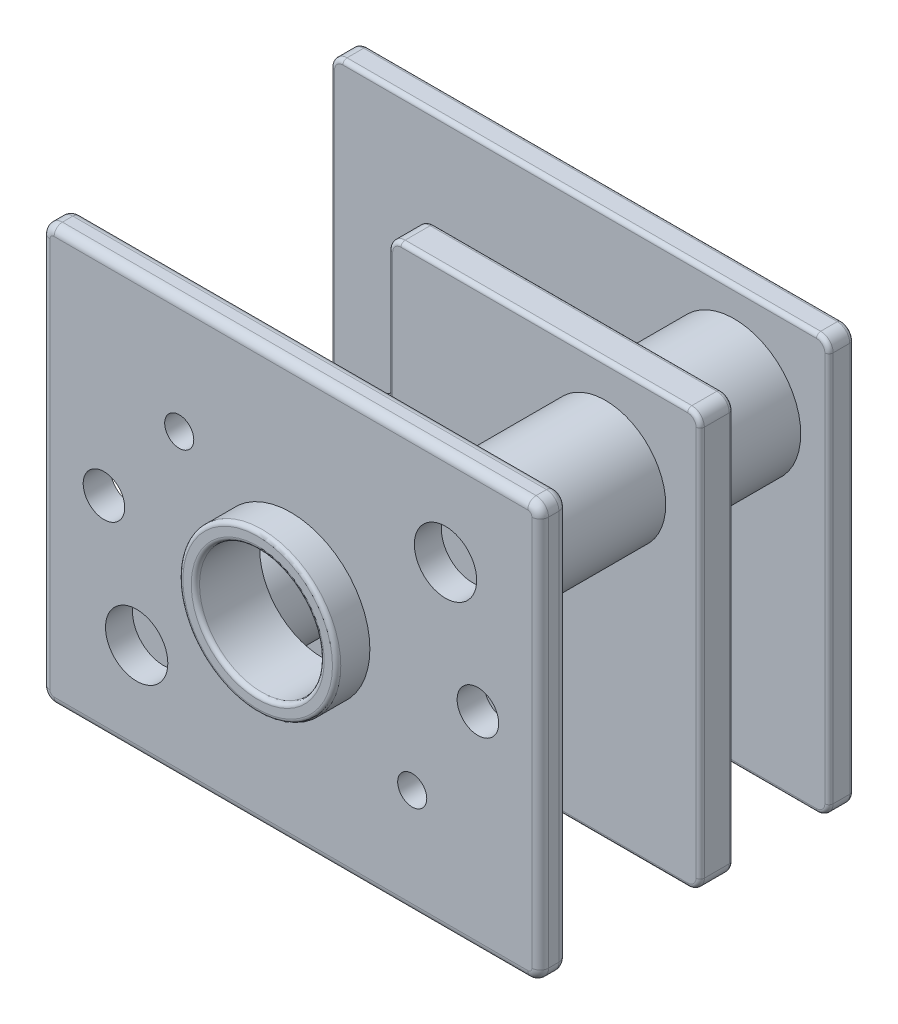
SolidWorks part; units mm, degrees
ref_plane "Front Plane" through (0, 0, 0) normal (0, 0, 1) x (1, 0, 0)
ref_plane "Top Plane" through (0, 0, 0) normal (0, 1, 0) x (1, 0, 0)
ref_plane "Right Plane" through (0, 0, 0) normal (1, 0, 0) x (0, 0, -1)
sketch "Sketch1" plane through (0, 0, 0) normal (0, 0, 1) x (1, 0, 0)
  line L0 (0.369, -5) -> (6, -5)
  line L1 (-6, 5) -> (6, 5)
  line L2 (-6, 5) -> (-6, -5)
  line L3 (-6, -5) -> (-0.369, -5)
  line L4 (6, 5) -> (6, -5)
  line L5 (-6, 5) -> (6, -5) construction
  line L6 (-6, -5) -> (6, 5) construction
  arc A0 (0.369, -5) -> (-0.369, -5) centre (0, -5) ccw
  point P0 (0, 0)
extrude "Boss-Extrude1" add sketch "Sketch1" along normal blind 0.6
fillet "Fillet1" radius 0.3 4 edges at (-6, 5, 0.3) (6, 5, 0.3) (6, -5, 0.3) (-6, -5, 0.3)
fillet "Fillet2" radius 0.1 20 edges at (3.0345, -5, 0) (5.9121, -4.9121, 0) (6, 0, 0) (5.9121, 4.9121, 0) (0, 5, 0) (-5.9121, 4.9121, 0) (-6, 0, 0) (-5.9121, -4.9121, 0) (3.0345, -5, 0.6) (5.9121, -4.9121, 0.6) (6, 0, 0.6) (5.9121, 4.9121, 0.6) (0, 5, 0.6) (-5.9121, 4.9121, 0.6) (-6, 0, 0.6) (-5.9121, -4.9121, 0.6) (0, -4.631, 0) (-3.0345, -5, 0) (0, -4.631, 0.6) (-3.0345, -5, 0.6)
sketch "Sketch2" plane through (0, 0, 0.6) normal (0, 0, 1) x (1, 0, 0)
  line L0 (-5.8414, -4.8414) -> (-3.1772, -2.1942)
  line L1 (5.8414, 4.8414) -> (3.7201, 2.7201)
  arc A2 (-5.9, -4.7) -> (-5.7, -4.9) centre (-5.7, -4.7) ccw construction
  arc A3 (5.9, 4.7) -> (5.7, 4.9) centre (5.7, 4.7) ccw construction
  circle A4 centre (-3.7133, -2.7269) radius 1.6
  circle A5 centre (3.7201, 2.7201) radius 1.6
  dimension "D1" = 3.2
  dimension "D2" = 3
  dimension "D3" = 3
extrude "Boss-Extrude2" add sketch "Sketch2" along normal blind 2.3
sketch "Sketch3" plane through (0, 0, 2.9) normal (0, 0, 1) x (1, 0, 0)
  line L0 (-6, -5) -> (6, -5)
  line L4 (-6, 0.3) -> (-1.5, 0.3)
  line L5 (0.369, -5) -> (6, -5)
  line L6 (6, -5) -> (6, 5)
  line L7 (6, 5) -> (-6, 5)
  line L8 (-6, 5) -> (-6, -5)
  line L9 (-6, -5) -> (-0.369, -5)
  line L10 (-1.5, 5) -> (-1.5, 0.3)
  line L11 (6, -5) -> (6, 5)
  line L12 (6, 5) -> (-1.5, 5)
  line L13 (-6, 0.3) -> (-6, -5)
  arc A1 (0.369, -5) -> (-0.369, -5) centre (0, -5) ccw
  dimension "D2" = 4.5
  dimension "D3" = 4.7
  dimension "D1" = 0
extrude "Boss-Extrude3" add sketch "Sketch3" along normal blind 0.8
fillet "Fillet3" radius 0.3 6 edges at (6, 5, 3.3) (6, -5, 3.3) (-6, -5, 3.3) (-1.5, 0.3, 3.3) (-6, 0.3, 3.3) (-1.5, 5, 3.3)
fillet "Fillet4" radius 0.1 24 edges at (5.9121, 4.9121, 2.9) (6, 0, 2.9) (5.9121, -4.9121, 2.9) (0, -5, 2.9) (-5.9121, -4.9121, 2.9) (-6, -2.35, 2.9) (-5.9121, 0.2121, 2.9) (-3.75, 0.3, 2.9) (-1.5879, 0.3879, 2.9) (-1.5, 2.65, 2.9) (-1.4121, 4.9121, 2.9) (5.9121, 4.9121, 3.7) (6, 0, 3.7) (5.9121, -4.9121, 3.7) (0, -5, 3.7) (-5.9121, -4.9121, 3.7) (-6, -2.35, 3.7) (-5.9121, 0.2121, 3.7) (-3.75, 0.3, 3.7) (-1.5879, 0.3879, 3.7) (-1.5, 2.65, 3.7) (-1.4121, 4.9121, 3.7) (2.25, 5, 2.9) (2.25, 5, 3.7)
sketch "Sketch4" plane through (0, 0, 3.7) normal (0, 0, 1) x (1, 0, 0)
  circle A2 centre (3.7201, 2.7201) radius 1.45
  circle A3 centre (-3.7133, -2.7269) radius 1.45
  dimension "D1" = 2.9
extrude "Boss-Extrude4" add sketch "Sketch4" along normal blind 3.2
sketch "Sketch5" plane through (0, 0, 6.9) normal (0, 0, 1) x (1, 0, 0)
  line L0 (-6, -5) -> (6, -5)
  line L1 (0, 0) -> (4.5, 0) construction
  line L2 (0, 0) -> (-4.5, 0) construction
  line L3 (0, 0) -> (2.9192, -2.4327) construction
  line L4 (0, 0) -> (-2.6888, 2.2406) construction
  line L5 (0.369, -5) -> (6, -5)
  line L6 (6, -5) -> (6, 5)
  line L7 (6, 5) -> (-6, 5)
  line L8 (-6, 5) -> (-6, -5)
  line L9 (-6, -5) -> (-0.369, -5)
  line L11 (6, -5) -> (6, 5)
  line L12 (6, 5) -> (-6, 5)
  line L13 (-6, 5) -> (-6, -5)
  arc A1 (0.369, -5) -> (-0.369, -5) centre (0, -5) ccw
  circle A2 centre (3.7201, 2.7201) radius 0.75
  circle A4 centre (-3.7133, -2.7269) radius 0.75
  circle A5 centre (4.5, 0) radius 0.5
  circle A6 centre (-4.5, 0) radius 0.5
  circle A7 centre (2.9192, -2.4327) radius 0.35
  circle A8 centre (-2.6888, 2.2406) radius 0.35
  circle A9 centre (0, 0) radius 1.5
  dimension "D2" = 1.5
  dimension "D5" = 1
  dimension "D8" = 0.7
  dimension "D9" = 3
  dimension "D3" = 4.5
  dimension "D4" = 4.5
  dimension "D6" = 3.5
  dimension "D7" = 3.8
  dimension "D1" = 0
extrude "Boss-Extrude5" add sketch "Sketch5" along normal blind 0.65
fillet "Fillet5" radius 0.3 4 edges at (6, -5, 7.225) (-6, -5, 7.225) (-6, 5, 7.225) (6, 5, 7.225)
fillet "Fillet6" radius 0.2 16 edges at (5.9121, 4.9121, 7.55) (6, 0, 7.55) (5.9121, -4.9121, 7.55) (0, -5, 7.55) (-5.9121, -4.9121, 7.55) (-6, 0, 7.55) (-5.9121, 4.9121, 7.55) (5.9121, 4.9121, 6.9) (6, 0, 6.9) (5.9121, -4.9121, 6.9) (0, -5, 6.9) (-5.9121, -4.9121, 6.9) (-6, 0, 6.9) (-5.9121, 4.9121, 6.9) (0, 5, 7.55) (0, 5, 6.9)
sketch "Sketch6" plane through (0, 0, 7.55) normal (0, 0, 1) x (1, 0, 0)
  circle A0 centre (0, 0) radius 1.5 construction
  circle A1 centre (0, 0) radius 1.5
  circle A2 centre (0, 0) radius 1.9
  dimension "D1" = 3.8
extrude "Boss-Extrude6" add sketch "Sketch6" along normal blind 0.8
fillet "Fillet7" radius 0.1 2 edges at (1.5, 0, 8.35) (1.9, 0, 8.35)
sketch "Sketch7" plane through (0, 0, 6.9) normal (0, 0, -1) x (-1, 0, 0)
  circle A1 centre (0, 0) radius 1.9
  circle A2 centre (0, 0) radius 1.9
  circle A3 centre (0, 0) radius 1.5
  circle A4 centre (0, 0) radius 1.5
  dimension "D1" = 0
  dimension "D2" = 0
extrude "Boss-Extrude7" add sketch "Sketch7" along normal blind 0.1
